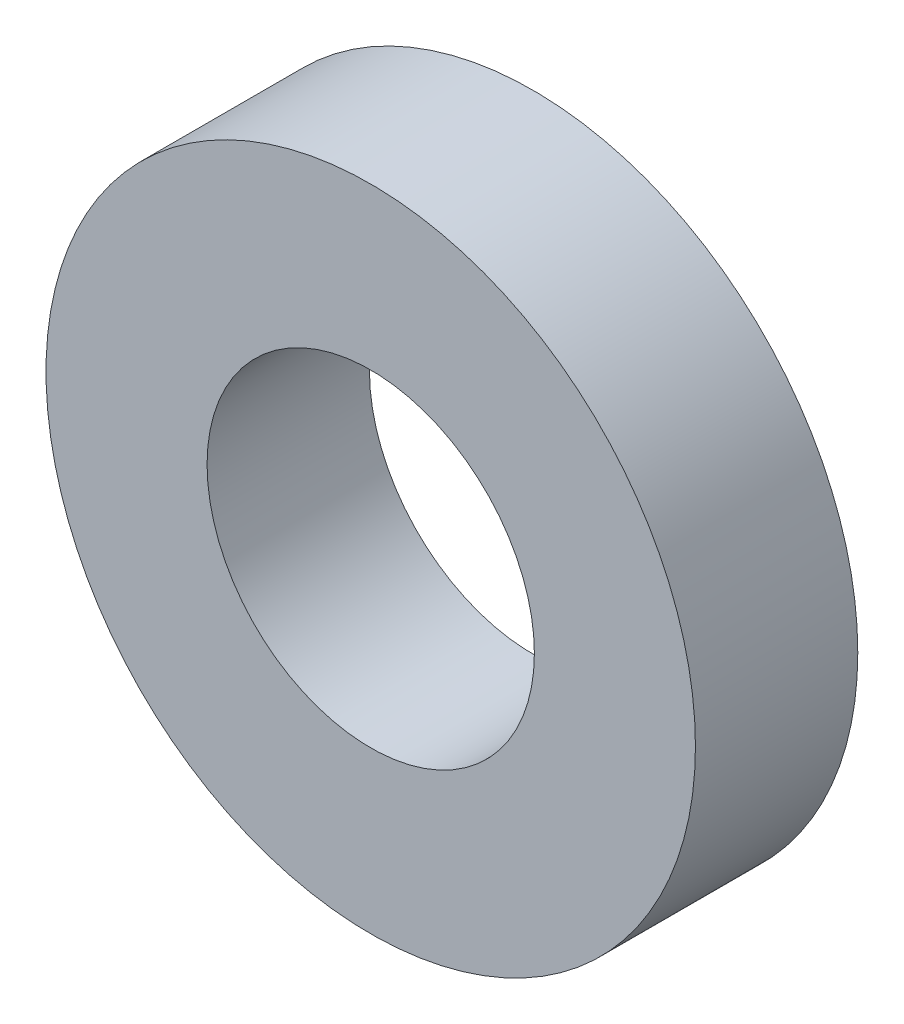
SolidWorks part; units mm, degrees
ref_plane "Front Plane" through (0, 0, 0) normal (0, 0, 1) x (1, 0, 0)
ref_plane "Top Plane" through (0, 0, 0) normal (0, 1, 0) x (1, 0, 0)
ref_plane "Right Plane" through (0, 0, 0) normal (1, 0, 0) x (0, 0, -1)
sketch "Sketch1" plane through (0, 0, 0) normal (0, 0, 1) x (1, 0, 0)
  circle A0 centre (0, 0) radius 6.35
  circle A1 centre (0, 0) radius 3.2004
  dimension "OD" = 12.7
  dimension "ID" = 6.4008
extrude "Extrude1" add sketch "Sketch1" along normal mid plane 3.175
sketch "Sketch2" plane through (0, 0, 0) normal (1, 0, 0) x (0, 0, -1)
  line L0 (-1.5875, -3.2004) -> (1.5875, -3.2004) construction
  line L3 (1.5875, 3.2004) -> (-1.5875, 3.2004) construction
  line L5 (-1.5875, -3.2004) -> (1.5875, -3.2004)
  line L6 (1.5875, 3.2004) -> (-1.5875, 3.2004)
sketch "Sketch4" plane through (0, 0, 1.5875) normal (0, 0, 1) x (1, 0, 0)
  line L0 (0, 0) -> (-2.263, 2.263)
  line L1 (0, -3.4925) -> (0, 3.4925) construction
  circle A0 centre (0, 0) radius 3.2004 construction
  dimension "D1" = 45
